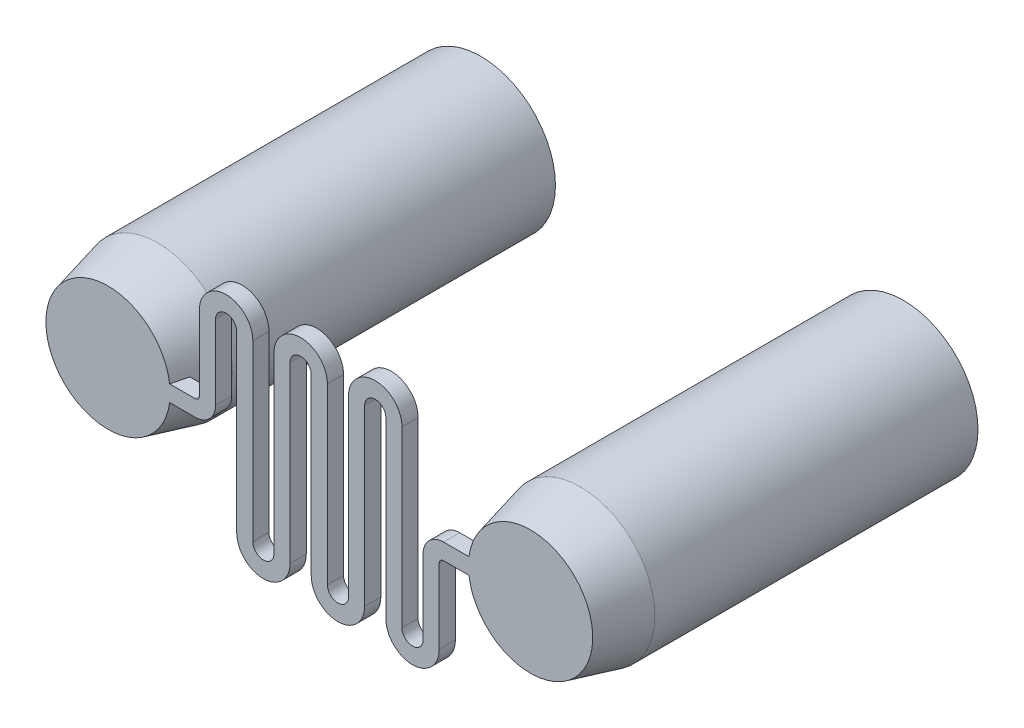
SolidWorks part; units mm, degrees
ref_plane "Front Plane" through (0, 0, 0) normal (0, 0, 1) x (1, 0, 0)
ref_plane "Top Plane" through (0, 0, 0) normal (0, 1, 0) x (1, 0, 0)
ref_plane "Right Plane" through (0, 0, 0) normal (1, 0, 0) x (0, 0, -1)
sketch "Sketch2" plane through (0, 0, 0) normal (0, 0, 1) x (1, 0, 0)
  line L3 (-20.5, -0.65) -> (-13.5, -0.65)
  line L6 (-11.85, 1) -> (-11.85, 7)
  line L9 (-10.15, 7) -> (-10.15, 0)
  line L12 (-10.15, 0) -> (-10.15, -7)
  line L15 (-5.85, -7) -> (-5.85, 0)
  line L18 (-5.85, 0) -> (-5.85, 7)
  line L21 (-4.15, 7) -> (-4.15, 0)
  line L22 (-4.15, 0) -> (-4.15, -7)
  line L23 (0.15, -7) -> (0.15, 0)
  line L24 (0.15, 0) -> (0.15, 7)
  line L25 (1.85, 7) -> (1.85, 0)
  line L26 (1.85, 0) -> (1.85, -7)
  line L27 (6.15, -7) -> (6.15, -1)
  line L28 (6.5, -0.65) -> (13.5, -0.65)
  line L29 (-20.5, 0.65) -> (-13.5, 0.65)
  line L30 (-13.15, 1) -> (-13.15, 7)
  line L31 (-8.85, 7) -> (-8.85, 0)
  line L32 (-8.85, 0) -> (-8.85, -7)
  line L33 (-7.15, -7) -> (-7.15, 0)
  line L34 (-7.15, 0) -> (-7.15, 7)
  line L35 (-2.85, 7) -> (-2.85, 0)
  line L36 (-2.85, 0) -> (-2.85, -7)
  line L37 (-1.15, -7) -> (-1.15, 0)
  line L38 (-1.15, 0) -> (-1.15, 7)
  line L39 (3.15, 7) -> (3.15, 0)
  line L40 (3.15, 0) -> (3.15, -7)
  line L41 (4.85, -7) -> (4.85, -1)
  line L42 (6.5, 0.65) -> (13.5, 0.65)
  arc A8 (-11.85, 1) -> (-13.5, -0.65) centre (-13.5, 1) cw
  arc A9 (-11.85, 7) -> (-10.15, 7) centre (-11, 7) cw
  arc A10 (-10.15, -7) -> (-5.85, -7) centre (-8, -7) ccw
  arc A11 (-5.85, 7) -> (-4.15, 7) centre (-5, 7) cw
  arc A12 (-4.15, -7) -> (0.15, -7) centre (-2, -7) ccw
  arc A13 (0.15, 7) -> (1.85, 7) centre (1, 7) cw
  arc A14 (1.85, -7) -> (6.15, -7) centre (4, -7) ccw
  arc A15 (6.15, -1) -> (6.5, -0.65) centre (6.5, -1) cw
  arc A16 (-13.15, 1) -> (-13.5, 0.65) centre (-13.5, 1) cw
  arc A17 (-13.15, 7) -> (-8.85, 7) centre (-11, 7) cw
  arc A18 (-8.85, -7) -> (-7.15, -7) centre (-8, -7) ccw
  arc A19 (-7.15, 7) -> (-2.85, 7) centre (-5, 7) cw
  arc A20 (-2.85, -7) -> (-1.15, -7) centre (-2, -7) ccw
  arc A21 (-1.15, 7) -> (3.15, 7) centre (1, 7) cw
  arc A22 (3.15, -7) -> (4.85, -7) centre (4, -7) ccw
  arc A23 (4.85, -1) -> (6.5, 0.65) centre (6.5, -1) cw
  arc A24 (-20.5, 0.65) -> (-20.5, -0.65) centre (-20.5, 0) ccw
  arc A25 (13.5, -0.65) -> (13.5, 0.65) centre (13.5, 0) ccw
  point P4 (0, 0)
  point P32 (5.5, 0)
  point P35 (-12.5, 0)
  dimension "D1" = 8
  dimension "D14" = 8
extrude "Boss-Extrude1" add sketch "Sketch2" along normal blind 1.3
ref_plane "Plane1" through (0, 0, 0) normal (0, 1, 0) x (1, 0, 0)
sketch "Sketch3" plane through (0, 0, 0) normal (0, 1, 0) x (1, 0, 0)
  line L0 (-20.5, -1.3) -> (-25.5, -1.3)
  line L2 (-20.5, -1.3) -> (-20.5, 28.7)
  line L3 (-20.5, 28.7) -> (-26.5, 28.7)
  line L4 (-26.5, 28.7) -> (-26.5, 2.7)
  line L5 (-26.5, 2.7) -> (-25.5, -1.3)
  dimension "D1" = 5
  dimension "D3" = 30
  dimension "D4" = 6
revolve "Revolve1" add sketch "Sketch3" angle 360 about L2
ref_plane "Plane2" through (0, 0, 0) normal (0, 1, 0) x (1, 0, 0)
sketch "Sketch4" plane through (0, 0, 0) normal (0, 1, 0) x (1, 0, 0)
  line L0 (13.5, -1.3) -> (18.5, -1.3)
  line L2 (13.5, -1.3) -> (13.5, 28.7)
  line L3 (13.5, 28.7) -> (19.5, 28.7)
  line L4 (19.5, 28.7) -> (19.5, 2.7)
  line L5 (19.5, 2.7) -> (18.5, -1.3)
  dimension "D1" = 5
  dimension "D3" = 30
  dimension "D4" = 6
revolve "Revolve2" add sketch "Sketch4" angle 360 about L2
sketch "Sketch5" plane through (0, 0, -28.7) normal (0, 0, -1) x (-1, 0, 0)
  circle A0 centre (20.5, 0) radius 5
  circle A1 centre (-13.5, 0) radius 5
  dimension "D1" = 10
  dimension "D2" = 10
extrude "Cut-Extrude1" cut sketch "Sketch5" against normal blind 28
